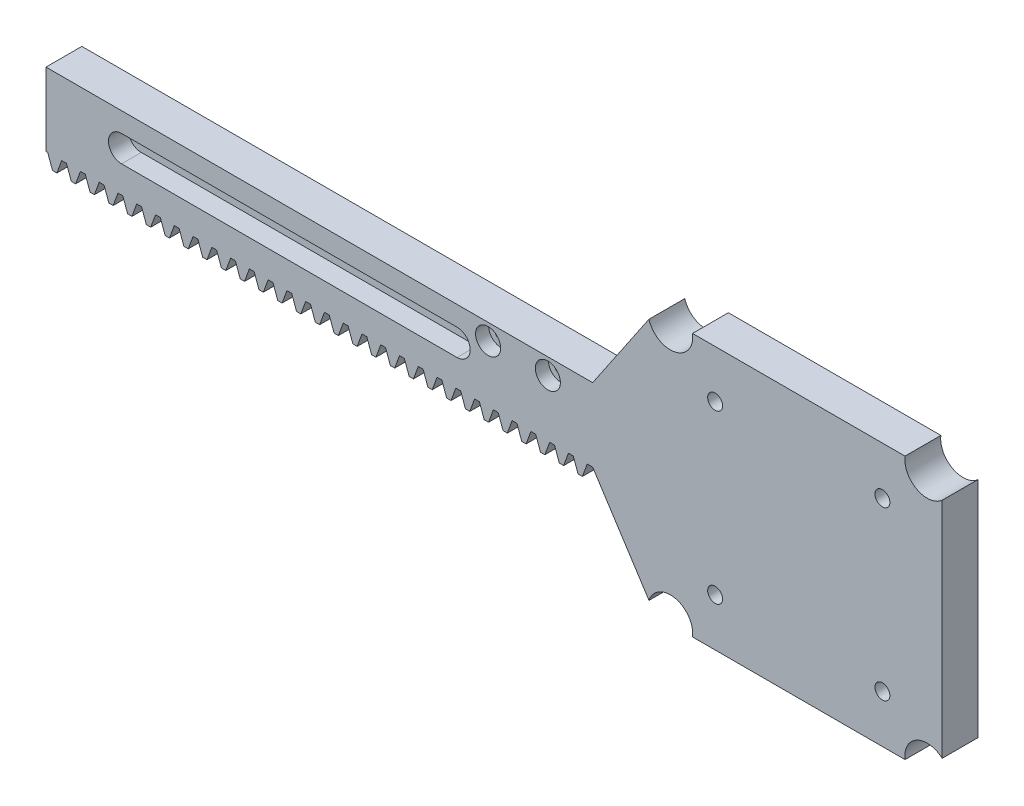
SolidWorks part; units mm, degrees
ref_plane "前视基准面" through (0, 0, 0) normal (0, 0, 1) x (1, 0, 0)
ref_plane "上视基准面" through (0, 0, 0) normal (0, 1, 0) x (1, 0, 0)
ref_plane "右视基准面" through (0, 0, 0) normal (1, 0, 0) x (0, 0, -1)
other "Configuration Table"
sketch "M1 rack with integral 48 x 44 mm seat flange profile" plane through (0, 0, 0) normal (0, 0, 1) x (1, 0, 0)
  line L0 (-69, 10.26) -> (-68.7132, 10.26)
  line L1 (-68.7132, 10.26) -> (-67.9089, 8.05)
  line L2 (-67.9089, 8.05) -> (-67.1796, 8.05)
  line L3 (-67.1796, 8.05) -> (-66.3752, 10.26)
  line L4 (-66.3752, 10.26) -> (-65.5717, 10.26)
  line L5 (-65.5717, 10.26) -> (-64.7673, 8.05)
  line L6 (-64.7673, 8.05) -> (-64.038, 8.05)
  line L7 (-64.038, 8.05) -> (-63.2336, 10.26)
  line L8 (-63.2336, 10.26) -> (-62.4301, 10.26)
  line L9 (-62.4301, 10.26) -> (-61.6257, 8.05)
  line L10 (-61.6257, 8.05) -> (-60.8964, 8.05)
  line L11 (-60.8964, 8.05) -> (-60.0921, 10.26)
  line L12 (-60.0921, 10.26) -> (-59.2885, 10.26)
  line L13 (-59.2885, 10.26) -> (-58.4841, 8.05)
  line L14 (-58.4841, 8.05) -> (-57.7548, 8.05)
  line L15 (-57.7548, 8.05) -> (-56.9505, 10.26)
  line L16 (-56.9505, 10.26) -> (-56.1469, 10.26)
  line L17 (-56.1469, 10.26) -> (-55.3425, 8.05)
  line L18 (-55.3425, 8.05) -> (-54.6132, 8.05)
  line L19 (-54.6132, 8.05) -> (-53.8089, 10.26)
  line L20 (-53.8089, 10.26) -> (-53.0053, 10.26)
  line L21 (-53.0053, 10.26) -> (-52.2009, 8.05)
  line L22 (-52.2009, 8.05) -> (-51.4717, 8.05)
  line L23 (-51.4717, 8.05) -> (-50.6673, 10.26)
  line L24 (-50.6673, 10.26) -> (-49.8637, 10.26)
  line L25 (-49.8637, 10.26) -> (-49.0593, 8.05)
  line L26 (-49.0593, 8.05) -> (-48.3301, 8.05)
  line L27 (-48.3301, 8.05) -> (-47.5257, 10.26)
  line L28 (-47.5257, 10.26) -> (-46.7221, 10.26)
  line L29 (-46.7221, 10.26) -> (-45.9177, 8.05)
  line L30 (-45.9177, 8.05) -> (-45.1885, 8.05)
  line L31 (-45.1885, 8.05) -> (-44.3841, 10.26)
  line L32 (-44.3841, 10.26) -> (-43.5805, 10.26)
  line L33 (-43.5805, 10.26) -> (-42.7761, 8.05)
  line L34 (-42.7761, 8.05) -> (-42.0469, 8.05)
  line L35 (-42.0469, 8.05) -> (-41.2425, 10.26)
  line L36 (-41.2425, 10.26) -> (-40.4389, 10.26)
  line L37 (-40.4389, 10.26) -> (-39.6345, 8.05)
  line L38 (-39.6345, 8.05) -> (-38.9053, 8.05)
  line L39 (-38.9053, 8.05) -> (-38.1009, 10.26)
  line L40 (-38.1009, 10.26) -> (-37.2973, 10.26)
  line L41 (-37.2973, 10.26) -> (-36.4929, 8.05)
  line L42 (-36.4929, 8.05) -> (-35.7637, 8.05)
  line L43 (-35.7637, 8.05) -> (-34.9593, 10.26)
  line L44 (-34.9593, 10.26) -> (-34.1557, 10.26)
  line L45 (-34.1557, 10.26) -> (-33.3513, 8.05)
  line L46 (-33.3513, 8.05) -> (-32.6221, 8.05)
  line L47 (-32.6221, 8.05) -> (-31.8177, 10.26)
  line L48 (-31.8177, 10.26) -> (-31.0141, 10.26)
  line L49 (-31.0141, 10.26) -> (-30.2098, 8.05)
  line L50 (-30.2098, 8.05) -> (-29.4805, 8.05)
  line L51 (-29.4805, 8.05) -> (-28.6761, 10.26)
  line L52 (-28.6761, 10.26) -> (-27.8725, 10.26)
  line L53 (-27.8725, 10.26) -> (-27.0682, 8.05)
  line L54 (-27.0682, 8.05) -> (-26.3389, 8.05)
  line L55 (-26.3389, 8.05) -> (-25.5345, 10.26)
  line L56 (-25.5345, 10.26) -> (-24.7309, 10.26)
  line L57 (-24.7309, 10.26) -> (-23.9266, 8.05)
  line L58 (-23.9266, 8.05) -> (-23.1973, 8.05)
  line L59 (-23.1973, 8.05) -> (-22.3929, 10.26)
  line L60 (-22.3929, 10.26) -> (-21.5894, 10.26)
  line L61 (-21.5894, 10.26) -> (-20.785, 8.05)
  line L62 (-20.785, 8.05) -> (-20.0557, 8.05)
  line L63 (-20.0557, 8.05) -> (-19.2514, 10.26)
  line L64 (-19.2514, 10.26) -> (-18.4478, 10.26)
  line L65 (-18.4478, 10.26) -> (-17.6434, 8.05)
  line L66 (-17.6434, 8.05) -> (-16.9141, 8.05)
  line L67 (-16.9141, 8.05) -> (-16.1098, 10.26)
  line L68 (-16.1098, 10.26) -> (-15.3062, 10.26)
  line L69 (-15.3062, 10.26) -> (-14.5018, 8.05)
  line L70 (-14.5018, 8.05) -> (-13.7725, 8.05)
  line L71 (-13.7725, 8.05) -> (-12.9682, 10.26)
  line L72 (-12.9682, 10.26) -> (-12.1646, 10.26)
  line L73 (-12.1646, 10.26) -> (-11.3602, 8.05)
  line L74 (-11.3602, 8.05) -> (-10.6309, 8.05)
  line L75 (-10.6309, 8.05) -> (-9.8266, 10.26)
  line L76 (-9.8266, 10.26) -> (-9.023, 10.26)
  line L77 (-9.023, 10.26) -> (-8.2186, 8.05)
  line L78 (-8.2186, 8.05) -> (-7.4894, 8.05)
  line L79 (-7.4894, 8.05) -> (-6.685, 10.26)
  line L80 (-6.685, 10.26) -> (-5.8814, 10.26)
  line L81 (-5.8814, 10.26) -> (-5.077, 8.05)
  line L82 (-5.077, 8.05) -> (-4.3478, 8.05)
  line L83 (-4.3478, 8.05) -> (-3.5434, 10.26)
  line L84 (-3.5434, 10.26) -> (-2.7398, 10.26)
  line L85 (-2.7398, 10.26) -> (-1.9354, 8.05)
  line L86 (-1.9354, 8.05) -> (-1.2062, 8.05)
  line L87 (-1.2062, 8.05) -> (-0.4018, 10.26)
  line L88 (-0.4018, 10.26) -> (0.4018, 10.26)
  line L89 (0.4018, 10.26) -> (1.2062, 8.05)
  line L90 (1.2062, 8.05) -> (1.9354, 8.05)
  line L91 (1.9354, 8.05) -> (2.7398, 10.26)
  line L92 (2.7398, 10.26) -> (3.5434, 10.26)
  line L93 (3.5434, 10.26) -> (4.3478, 8.05)
  line L94 (4.3478, 8.05) -> (5.077, 8.05)
  line L95 (5.077, 8.05) -> (5.8814, 10.26)
  line L96 (5.8814, 10.26) -> (6.685, 10.26)
  line L97 (6.685, 10.26) -> (7.4894, 8.05)
  line L98 (7.4894, 8.05) -> (8.2186, 8.05)
  line L99 (8.2186, 8.05) -> (9.023, 10.26)
  line L100 (9.023, 10.26) -> (9.8266, 10.26)
  line L101 (9.8266, 10.26) -> (10.6309, 8.05)
  line L102 (10.6309, 8.05) -> (11.3602, 8.05)
  line L103 (11.3602, 8.05) -> (12.1646, 10.26)
  line L104 (12.1646, 10.26) -> (12.9682, 10.26)
  line L105 (12.9682, 10.26) -> (13.7725, 8.05)
  line L106 (13.7725, 8.05) -> (14.5018, 8.05)
  line L107 (14.5018, 8.05) -> (15.3062, 10.26)
  line L108 (15.3062, 10.26) -> (16.1098, 10.26)
  line L109 (16.1098, 10.26) -> (16.9141, 8.05)
  line L110 (16.9141, 8.05) -> (17.6434, 8.05)
  line L111 (17.6434, 8.05) -> (18.4478, 10.26)
  line L112 (18.4478, 10.26) -> (19.2514, 10.26)
  line L113 (19.2514, 10.26) -> (20.0557, 8.05)
  line L114 (20.0557, 8.05) -> (20.785, 8.05)
  line L115 (20.785, 8.05) -> (21.5894, 10.26)
  line L116 (21.5894, 10.26) -> (22.5, 10.26)
  line L117 (22.5, 10.26) -> (33, -6)
  line L118 (33, -6) -> (79, -6)
  line L119 (79, -6) -> (81, -4)
  line L120 (81, -4) -> (81, 36)
  line L121 (81, 36) -> (79, 38)
  line L122 (79, 38) -> (33, 38)
  line L123 (33, 38) -> (22.5, 22.5)
  line L124 (22.5, 22.5) -> (-69, 22.5)
  line L125 (-69, 22.5) -> (-69, 10.26)
extrude "M1 rack with integral 48 x 44 mm seat flange" add sketch "M1 rack with integral 48 x 44 mm seat flange profile" along normal blind 6 from offset 40.4
sketch "56.55 mm stop slot profile" plane through (0, 0, 0) normal (0, 0, 1) x (1, 0, 0)
  line L0 (-56.3487, 14.8) -> (-0.2, 14.8)
  line L1 (-0.2, 19.2) -> (-56.3487, 19.2)
  arc A0 (-0.2, 14.8) -> (-0.2, 19.2) centre (-0.2, 17) ccw
  arc A1 (-56.3487, 19.2) -> (-56.3487, 14.8) centre (-56.3487, 17) ccw
extrude "56.55 mm stop slot" cut sketch "56.55 mm stop slot profile" along normal blind 3.4 from offset 43.1
sketch "Four M3 seat pilots - 28 x 28 pitch profile" plane through (0, 0, 0) normal (0, 0, 1) x (1, 0, 0)
  circle A0 centre (43, 2) radius 1.25
  circle A1 centre (43, 30) radius 1.25
  circle A2 centre (71, 2) radius 1.25
  circle A3 centre (71, 30) radius 1.25
extrude "Four M3 seat pilots - 28 x 28 pitch" cut sketch "Four M3 seat pilots - 28 x 28 pitch profile" along normal blind 6.2 from offset 40.3
sketch "Slide fastener bores profile" plane through (0, 0, 0) normal (0, 0, 1) x (1, 0, 0)
  circle A0 centre (5, 19.8) radius 1.1
  circle A1 centre (15, 19.8) radius 1.1
extrude "Slide fastener bores" cut sketch "Slide fastener bores profile" along normal blind 6.2 from offset 40.3
sketch "Slide screw recesses profile" plane through (0, 0, 0) normal (0, 0, 1) x (1, 0, 0)
  circle A0 centre (5, 19.8) radius 2.1
  circle A1 centre (15, 19.8) radius 2.1
extrude "Slide screw recesses" cut sketch "Slide screw recesses profile" along normal blind 2.3 from offset 44.2
sketch "Radar mounting screw tool access profile" plane through (0, 0, 0) normal (0, 0, 1) x (1, 0, 0)
  circle A0 centre (35.5, -5.5) radius 3.75
  circle A1 centre (35.5, 37.5) radius 3.75
  circle A2 centre (78.5, -5.5) radius 3.75
  circle A3 centre (78.5, 37.5) radius 3.75
extrude "Radar mounting screw tool access" cut sketch "Radar mounting screw tool access profile" along normal blind 6.2 from offset 40.3
